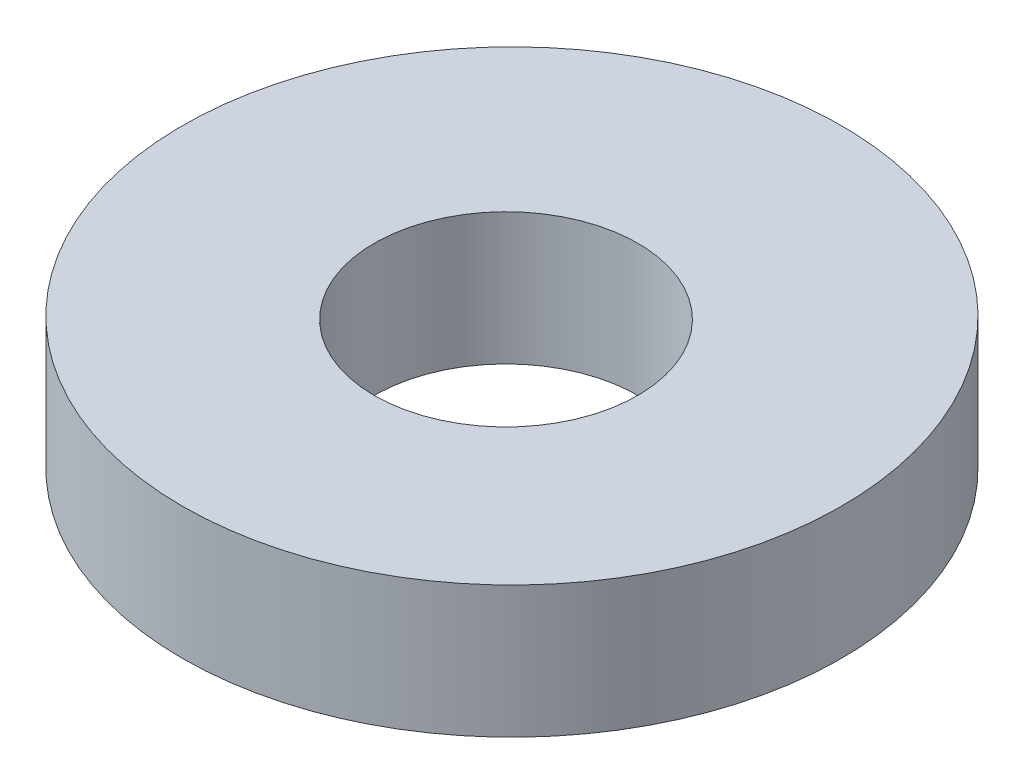
SolidWorks part; units mm, degrees
ref_plane "Front Plane" through (0, 0, 0) normal (0, 0, 1) x (1, 0, 0)
ref_plane "Top Plane" through (0, 0, 0) normal (0, 1, 0) x (1, 0, 0)
ref_plane "Right Plane" through (0, 0, 0) normal (1, 0, 0) x (0, 0, -1)
sketch "Sketch1" plane through (0, 0, 0) normal (0, 1, 0) x (1, 0, 0)
  circle A0 centre (0, 0) radius 12.5
  circle A1 centre (0, -0.2246) radius 5
  dimension "D1" = 25
  dimension "D2" = 10
extrude "Boss-Extrude1" add sketch "Sketch1" along normal blind 5
